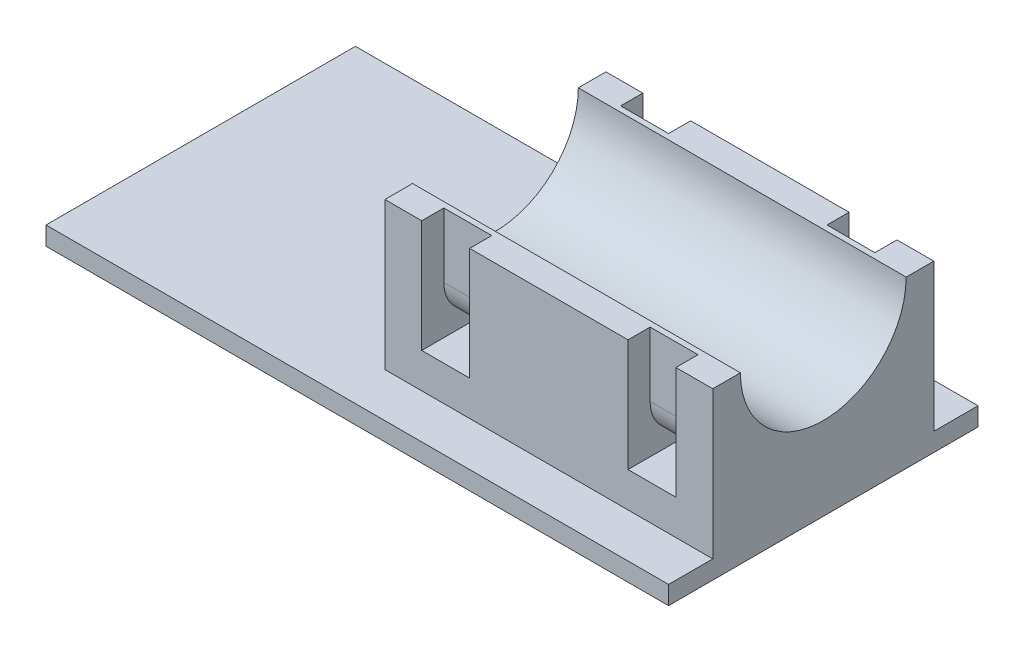
SolidWorks part; units mm, degrees
ref_plane "Front Plane" through (0, 0, 0) normal (0, 0, 1) x (1, 0, 0)
ref_plane "Top Plane" through (0, 0, 0) normal (0, 1, 0) x (1, 0, 0)
ref_plane "Right Plane" through (0, 0, 0) normal (1, 0, 0) x (0, 0, -1)
sketch "Sketch1" plane through (0, 0, 0) normal (0, 1, 0) x (1, 0, 0)
  line L1 (-84.5, -42) -> (84.5, -42)
  line L2 (-84.5, -42) -> (-84.5, 42)
  line L3 (-84.5, 42) -> (84.5, 42)
  line L4 (84.5, -42) -> (84.5, 42)
  line L5 (-84.5, -42) -> (84.5, 42) construction
  line L6 (-84.5, 42) -> (84.5, -42) construction
  point P0 (0, 0)
  dimension "D1" = 84
  dimension "D2" = 169
extrude "Boss-Extrude1" add sketch "Sketch1" along normal blind 5
sketch "Sketch2" plane through (0, 5, 0) normal (0, 1, 0) x (1, 0, 0)
  line L0 (84.5, -42) -> (84.5, 42) construction
  line L1 (-4.5, 30) -> (84.5, 30)
  line L2 (-4.5, 30) -> (-4.5, -30)
  line L3 (-4.5, -30) -> (84.5, -30)
  line L4 (84.5, 30) -> (84.5, -30)
  point P6 (-4.5, 0)
  dimension "D1" = 89
  dimension "D2" = 60
extrude "Boss-Extrude2" add sketch "Sketch2" along normal blind 40
sketch "Sketch3" plane through (-4.5, 0, 0) normal (-1, 0, 0) x (0, 0, 1)
  line L0 (-30, 45) -> (30, 45) construction
  line L1 (-22.5, 45) -> (22.5, 45)
  arc A0 (-22.5, 45) -> (22.5, 45) centre (0, 45) ccw
  point P3 (0, 45)
  dimension "D1" = 22.5
extrude "Cut-Extrude1" cut sketch "Sketch3" against normal through all
sketch "Sketch4" plane through (0, 0, -30) normal (0, 0, -1) x (-1, 0, 0)
  line L0 (4.5, 45) -> (4.5, 5) construction
  line L1 (-18.5, 17.5) -> (-5.5, 17.5)
  line L2 (-18.5, 17.5) -> (-18.5, 14.5)
  line L3 (-18.5, 14.5) -> (-5.5, 14.5)
  line L4 (-5.5, 17.5) -> (-5.5, 14.5)
  line L5 (-74.5, 17.5) -> (-61.5, 17.5)
  line L6 (-74.5, 17.5) -> (-74.5, 14.5)
  line L7 (-74.5, 14.5) -> (-61.5, 14.5)
  line L8 (-61.5, 17.5) -> (-61.5, 14.5)
  line L9 (-84.5, 45) -> (-84.5, 5) construction
  point P8 (0, 0)
  dimension "D1" = 13
  dimension "D2" = 3
  dimension "D3" = 5
  dimension "D4" = 10
  dimension "D5" = 10
extrude "Cut-Extrude2" cut sketch "Sketch4" against normal through all
sketch "Sketch6" plane through (0, 0, 30) normal (0, 0, 1) x (1, 0, 0)
  line L0 (-4.5, 45) -> (84.5, 45) construction
  line L1 (5.5, 17.5) -> (18.5, 17.5)
  line L2 (5.5, 17.5) -> (5.5, 45)
  line L3 (5.5, 45) -> (18.5, 45)
  line L4 (18.5, 17.5) -> (18.5, 45)
  line L6 (61.5, 17.5) -> (74.5, 17.5)
  line L7 (61.5, 17.5) -> (61.5, 45)
  line L8 (61.5, 45) -> (74.5, 45)
  line L9 (74.5, 17.5) -> (74.5, 45)
  point P7 (0, 0)
extrude "Cut-Extrude5" cut sketch "Sketch6" against normal blind 6
fillet "Fillet1" radius 10 2 edges at (68, 17.5, 24) (12, 17.5, 24)
mirror "Mirror1" about plane through (0, 0, 0) normal (0, 0, 1) of "Fillet1", "Cut-Extrude5"
